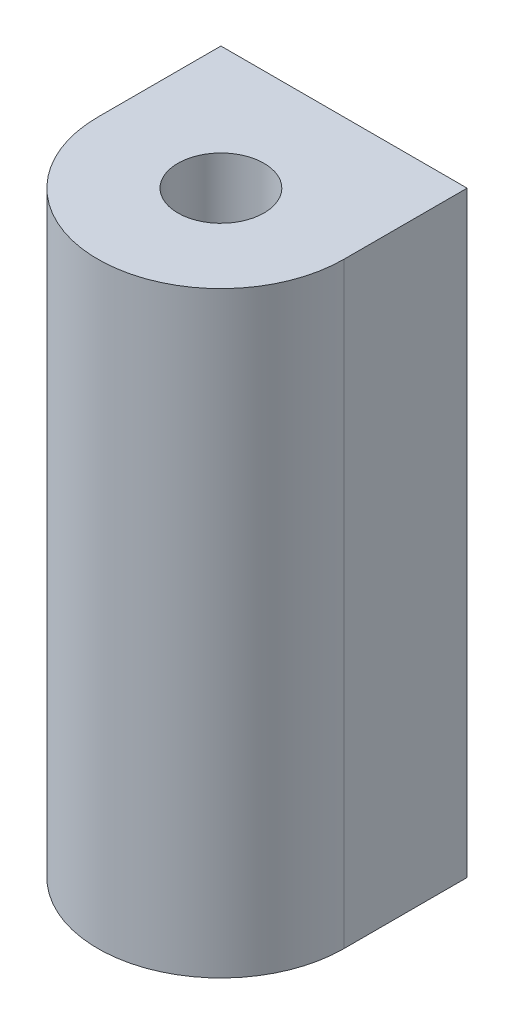
SolidWorks part; units mm, degrees
ref_plane "Front Plane" through (0, 0, 0) normal (0, 0, 1) x (1, 0, 0)
ref_plane "Top Plane" through (0, 0, 0) normal (0, 1, 0) x (1, 0, 0)
ref_plane "Right Plane" through (0, 0, 0) normal (1, 0, 0) x (0, 0, -1)
sketch "Sketch1" plane through (0, 0, 0) normal (0, 1, 0) x (1, 0, 0)
  line L0 (-4, 0) -> (-4, 4)
  line L1 (-4, 4) -> (4, 4)
  line L2 (4, 4) -> (4, 0)
  circle A0 centre (0, 0) radius 1.4
  arc A1 (-4, 0) -> (4, 0) centre (0, 0) ccw
  dimension "D1" = 2.8
  dimension "D2" = 8
extrude "Boss-Extrude1" add sketch "Sketch1" along normal blind 19.4
sketch "Sketch2" plane through (0, 0, -4) normal (0, 0, -1) x (-1, 0, 0)
  line L0 (-4, 19.4) -> (4, 19.4) construction
  line L1 (-1.4, 17.05) -> (1.4, 17.05)
  line L2 (-1.4, 17.05) -> (-1.4, 9.25)
  line L3 (-1.4, 9.25) -> (1.4, 9.25)
  line L4 (1.4, 17.05) -> (1.4, 9.25)
  line L5 (-1.4, 17.05) -> (1.4, 9.25) construction
  line L6 (-1.4, 9.25) -> (1.4, 17.05) construction
  point P0 (0, 13.15)
  point P7 (0, 0)
  dimension "D1" = 7.8
  dimension "D2" = 6.25
  dimension "D3" = 2.8
extrude "Boss-Extrude2" add sketch "Sketch2" along normal blind 1.8
